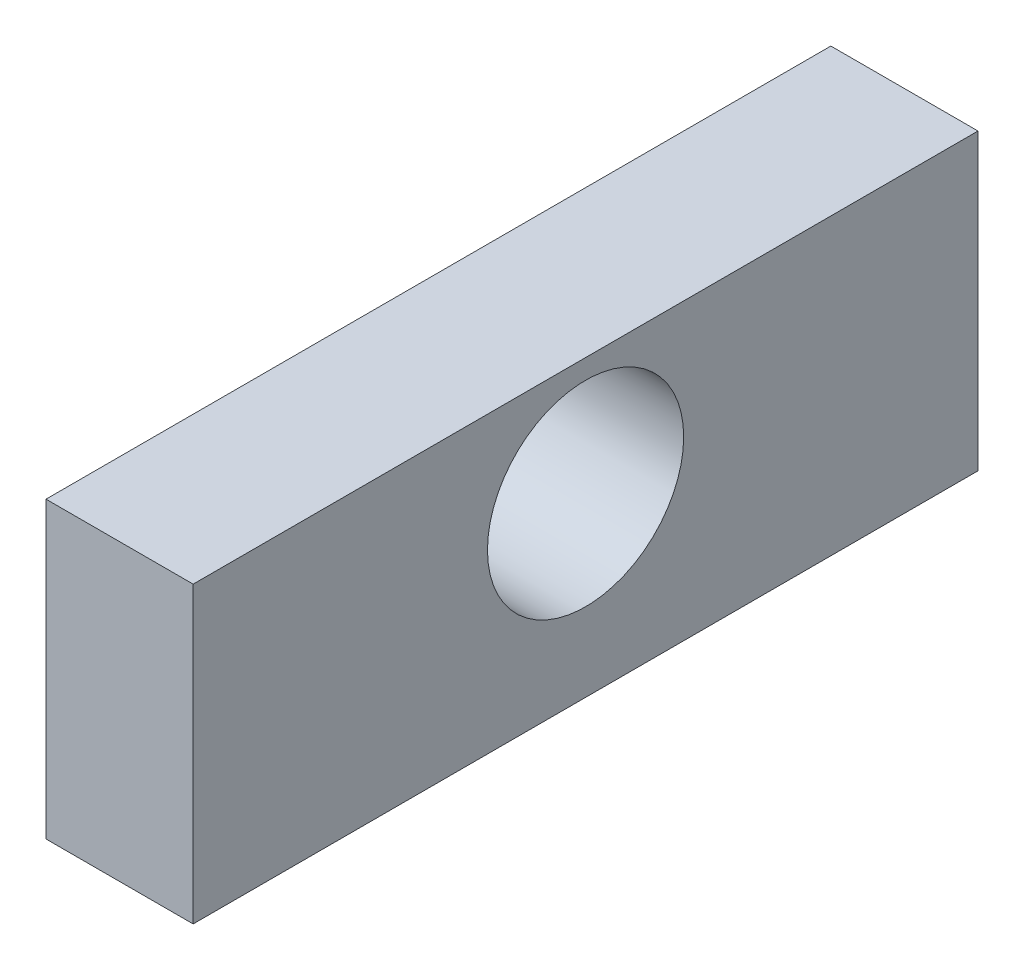
SolidWorks part; units mm, degrees
material "1060 Alloy"
ref_plane "Front Plane" through (0, 0, 0) normal (0, 0, 1) x (1, 0, 0)
ref_plane "Top Plane" through (0, 0, 0) normal (0, 1, 0) x (1, 0, 0)
ref_plane "Right Plane" through (0, 0, 0) normal (1, 0, 0) x (0, 0, -1)
sketch "Sketch1" plane through (0, 0, 0) normal (1, 0, 0) x (0, 0, -1)
  line L1 (-25.4, -9.525) -> (25.4, -9.525)
  line L2 (-25.4, -9.525) -> (-25.4, 9.525)
  line L3 (-25.4, 9.525) -> (25.4, 9.525)
  line L4 (25.4, -9.525) -> (25.4, 9.525)
  line L5 (-25.4, -9.525) -> (25.4, 9.525) construction
  line L6 (-25.4, 9.525) -> (25.4, -9.525) construction
  point P0 (0, 0)
  dimension "D1" = 50.8
  dimension "D2" = 19.05
extrude "Boss-Extrude1" add sketch "Sketch1" along normal blind 9.525
hole_wizard "1/2 (0.5) Diameter Hole1" positions "Sketch9" profile "Sketch8" hole size "1/2" standard "ANSI Inch"
sketch "Sketch9" plane through (9.525, 0, 0) normal (1, 0, 0) x (0, 0, -1)
  line L0 (-25.4, -9.525) -> (25.4, -9.525) construction
  point P0 (0, 1.905)
  dimension "D1" = 11.43
sketch "Sketch8" plane through (9.525, 1.905, 0) normal (0, 1, 0) x (0, 0, -1)
  line L0 (0, 0) -> (0, 73.9195)
  line L1 (0, 73.9195) -> (6.35, 70.104)
  line L2 (6.35, 70.104) -> (6.35, 0)
  line L5 (6.35, 0) -> (0, 0)
  line L10 (0, 73.9195) -> (-6.35, 70.104) construction
  line L11 (0, -6.35) -> (0, 107.95) construction
  dimension "Hole Dia." = 12.7
  dimension "Hole Depth" = 70.104
  dimension "Drill Angle" = 118
hole_wizard "#10-32 Tapped Hole1" positions "Sketch11" profile "Sketch10" tap size "#10-32" standard "ANSI Inch"
sketch "Sketch11" plane through (-1.0226, -1.0887, -25.4) normal (0, 0, -1) x (-1, 0, 0)
  line L0 (-10.5476, 10.6137) -> (-1.0226, 10.6137) construction
  line L2 (-10.5476, -8.4363) -> (-1.0226, -8.4363) construction
  line L3 (-10.5476, 10.6137) -> (-1.0226, 10.6137) construction
  point P0 (-5.7851, -2.0863)
  point P2 (-5.7851, 6.8037)
  point P6 (-5.7851, 10.6137)
  dimension "D1" = 0
  dimension "D2" = 0
  dimension "D3" = 3.81
  dimension "D4" = 6.35
cosmetic thread "Hole Thread1" parameters "D1"=9.652, "D2"=4.826
cosmetic thread "Hole Thread2" parameters "D1"=9.652, "D2"=4.826
sketch "Sketch10" plane through (4.7625, -3.175, -25.4) normal (1, 0, 0) x (0, 1, 0)
  line L0 (0, 0) -> (0, 13.1513)
  line L1 (0, 13.1513) -> (2.0193, 11.938)
  line L2 (2.0193, 11.938) -> (2.0193, 0)
  line L5 (2.0193, 0) -> (0, 0)
  line L10 (0, 13.1513) -> (-2.0193, 11.938) construction
  line L11 (0, -6.35) -> (0, 107.95) construction
  dimension "Tap Drill Dia." = 4.0386
  dimension "Tap Drill Depth" = 11.938
  dimension "Drill Angle" = 118
